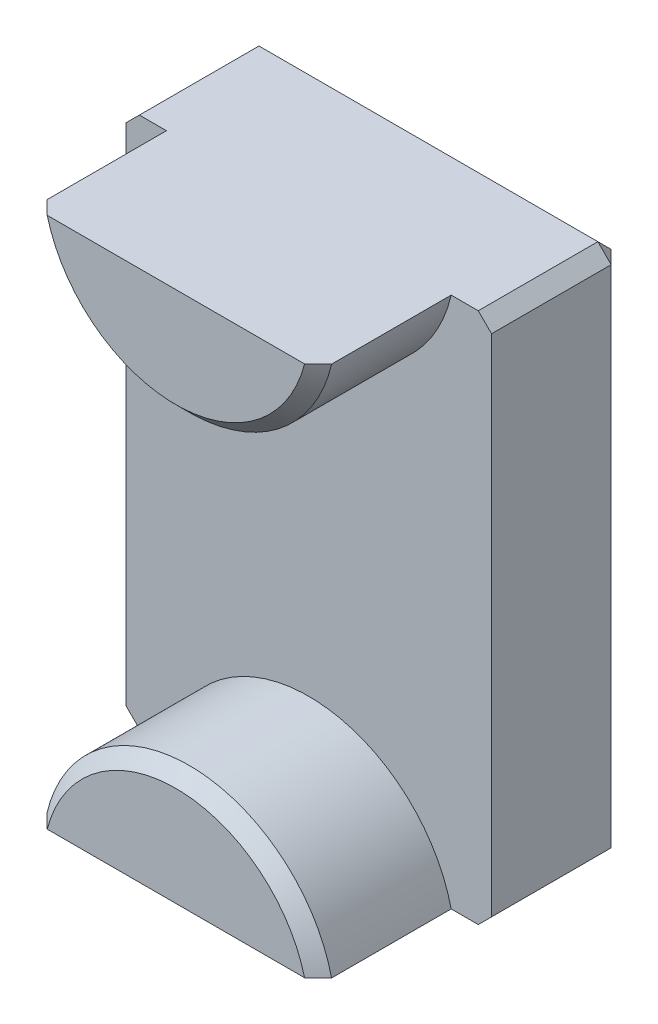
SolidWorks part; units mm, degrees
ref_plane "Front" through (0, 0, 0) normal (0, 0, 1) x (1, 0, 0)
ref_plane "Top" through (0, 0, 0) normal (0, 1, 0) x (1, 0, 0)
ref_plane "Right" through (0, 0, 0) normal (1, 0, 0) x (0, 0, -1)
sketch "Sketch1" plane through (0, 0, 0) normal (0, 0, 1) x (1, 0, 0)
  line L1 (-2.75, 4) -> (2.75, 4)
  line L2 (-2.75, 4) -> (-2.75, -4)
  line L3 (-2.75, -4) -> (2.75, -4)
  line L4 (2.75, 4) -> (2.75, -4)
  line L5 (-2.75, 4) -> (2.75, -4) construction
  line L6 (-2.75, -4) -> (2.75, 4) construction
  point P0 (0, 0)
extrude "Boss-Extrude1" add sketch "Sketch1" against normal blind 2
sketch "Sketch2" plane through (0, 0, 0) normal (0, 0, 1) x (1, 0, 0)
  line L0 (2.75, 4) -> (-2.75, 4) construction
  line L1 (2.75, 4) -> (-2.75, 4)
  circle A5 centre (0, 4.5) radius 2.3
  circle A6 centre (0, 4.5) radius 2.3 construction
  circle A8 centre (0, 4.5) radius 2.2
  circle A9 centre (0, 4.5) radius 2.2
  dimension "D1" = 0
  dimension "D2" = 0.1
extrude "Slot Tab" add sketch "Sketch2" along normal blind 2
mirror "Slot Tabs" about plane through (0, 0, 0) normal (0, 1, 0) of "Slot Tab"
chamfer "Deburs" distance 0.2 angle 45 10 edges at (0, 4, -2) (-2.75, 4, -1) (-2.75, 0, -2) (-2.75, -4, -1) (0, -4, -2) (2.75, -4, -1) (2.75, 0, -2) (2.75, 4, -1) (0, -2.3, 2) (0, 2.3, 2)
